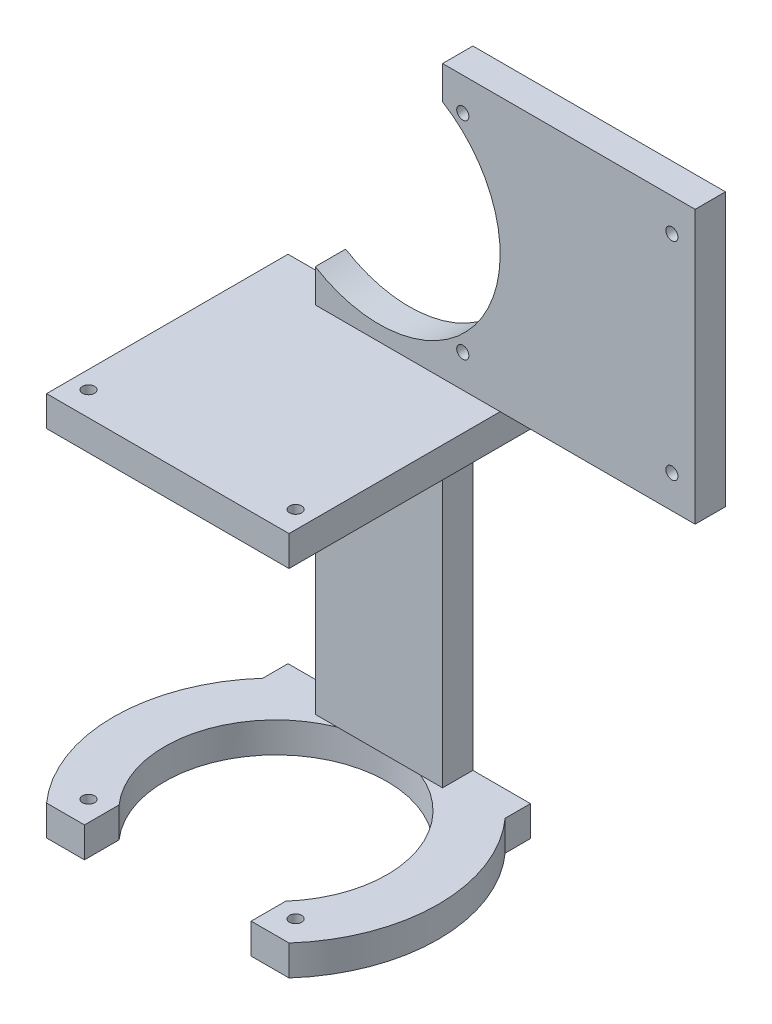
SolidWorks part; units mm, degrees
ref_plane "前视基准面" through (0, 0, 0) normal (0, 0, 1) x (1, 0, 0)
ref_plane "上视基准面" through (0, 0, 0) normal (0, 1, 0) x (1, 0, 0)
ref_plane "右视基准面" through (0, 0, 0) normal (1, 0, 0) x (0, 0, -1)
other "Configuration Table"
sketch "草图1" plane through (0, 0, 0) normal (0, 0, 1) x (1, 0, 0)
  line L1 (0, 0) -> (25, 0)
  line L2 (0, 0) -> (0, 27)
  line L3 (0, 27) -> (25, 27)
  line L4 (25, 0) -> (25, 27)
  dimension "D1" = 27
  dimension "D2" = 25
extrude "凸台-拉伸1" add sketch "草图1" along normal blind 3
sketch "草图2" plane through (0, 0, 3) normal (0, 0, 1) x (1, 0, 0)
  line L0 (0, 13.5) -> (50000, 13.5) construction
  line L1 (0, 27) -> (0, 0) construction
  line L3 (2, 23.75) -> (22.7, 23.75) construction
  line L4 (2, 23.75) -> (2, 3.25) construction
  line L5 (2, 3.25) -> (22.7, 3.25) construction
  line L6 (22.7, 23.75) -> (22.7, 3.25) construction
  circle A0 centre (2, 23.75) radius 0.6
  circle A1 centre (22.7, 23.75) radius 0.6
  circle A2 centre (22.7, 3.25) radius 0.6
  circle A3 centre (2, 3.25) radius 0.6
  circle A4 centre (-6.3, 13.5) radius 12
  point P4 (0, 13.5)
  point P9 (2, 13.5)
  dimension "D4" = 1.2
  dimension "D5" = 1.2
  dimension "D6" = 1.2
  dimension "D7" = 1.2
  dimension "D9" = 24
  dimension "D1" = 20.5
  dimension "D2" = 20.7
  dimension "D3" = 2
  dimension "D8" = 8.3
extrude "切除-拉伸1" cut sketch "草图2" against normal up to next and the other way through all
sketch "草图3" plane through (0, 0, 3) normal (0, 0, 1) x (1, 0, 0)
  line L0 (-6.3, 13.5) -> (-6.3, -49986.5) construction
  line L2 (-12.6, 3.2868) -> (0, 3.2868)
  line L3 (-12.6, 3.2868) -> (-12.6, -38.1)
  line L4 (-12.6, -38.1) -> (0, -38.1)
  line L5 (0, 3.2868) -> (0, 0)
  line L6 (0, 0) -> (25, 0)
  line L7 (25, 0) -> (25, 27)
  line L8 (25, 27) -> (0, 27)
  line L9 (0, 27) -> (0, 23.7132)
  line L10 (0, 3.2868) -> (0, 0)
  line L11 (0, 0) -> (25, 0)
  line L12 (25, 0) -> (25, 27)
  line L13 (25, 27) -> (0, 27)
  line L14 (0, 27) -> (0, 23.7132)
  line L15 (0, 3.2868) -> (0, -38.1)
  circle A0 centre (-6.3, 13.5) radius 12
  arc A1 (0, 3.2868) -> (0, 23.7132) centre (-6.3, 13.5) ccw
  arc A2 (0, 3.2868) -> (0, 23.7132) centre (-6.3, 13.5) ccw
  point P14 (-6.3, 3.2868)
  point P15 (0, 0)
  line M15 (0, 3.2868) -> (0, 0)
  dimension "D2" = 38.1
  dimension "D1" = 0
extrude "凸台-拉伸2" add sketch "草图3" against normal blind 3 contours A0 L0 L4 L15 M15 | L0 A0 L3 L4
sketch "草图4" plane through (0, 0, 3) normal (0, 0, 1) x (1, 0, 0)
  line L0 (-6.3, -21.7132) -> (-6.3, 49978.2868) construction
  line L1 (-12.6, -38.1) -> (0, -38.1) construction
  line L2 (0, 0) -> (25, 0) construction
  line L3 (-18.3, 0) -> (5.7, 0)
  line L4 (-18.3, 0) -> (-18.3, -3)
  line L5 (-18.3, -3) -> (5.7, -3)
  line L6 (5.7, 0) -> (5.7, -3)
  point P4 (-6.3, -38.1)
  point P9 (-6.3, 0)
  dimension "D1" = 24
  dimension "D2" = 3
  dimension "D3" = 0
extrude "凸台-拉伸3" add sketch "草图4" along normal blind 20.9 and the other way up to surface contours L4 L3 L6 L5 other way up to face at (1.4, 3.25, 0)
sketch "草图5" plane through (0, 0, 0) normal (0, 1, 0) x (1, 0, 0)
  line L0 (-6.3, -25) -> (-6.3, 49975) construction
  line L1 (5.7, -23.9) -> (-18.3, -23.9) construction
  line L3 (-16.55, -3) -> (3.95, -3) construction
  line L4 (-16.55, -3) -> (-16.55, -21.5) construction
  line L5 (-16.55, -21.5) -> (3.95, -21.5) construction
  line L6 (3.95, -3) -> (3.95, -21.5) construction
  line L7 (25, -3) -> (0, -3) construction
  circle A0 centre (-16.55, -21.5) radius 0.6
  circle A1 centre (3.95, -21.5) radius 0.6
  point P4 (-6.3, -23.9)
  point P10 (-6.3, -3)
  dimension "D2" = 1.2
  dimension "D3" = 1.2
  dimension "D1" = 18.5
  dimension "D4" = 20.5
extrude "切除-拉伸2" cut sketch "草图5" against normal up to next and the other way through all
ref_plane "基准面3" through (0, -19.05, 0) normal (0, -1, 0) x (-1, 0, 0)
mirror "镜向3" about plane through (0, -19.05, 0) normal (0, -1, 0) of "切除-拉伸2", "凸台-拉伸3"
sketch "草图9" plane through (0, -38.1, 0) normal (0, -1, 0) x (1, 0, 0)
  line L0 (-16.55, 21.5) -> (3.95, 21.5) construction
  line L1 (-6.3, 18.5) -> (-6.3, -49981.5) construction
  line L2 (-14.55, 23.9) -> (-14.55, 20.4758)
  line L3 (-18.3, 23.9) -> (5.7, 23.9) construction
  line L4 (1.95, 23.9) -> (1.95, 20.4758)
  line L5 (-14.55, 23.9) -> (1.95, 23.9)
  circle A0 centre (-6.3, 13.2) radius 11
  point P6 (-6.3, 21.5)
  line M8 (5.7, 23.9) -> (-18.3, 23.9)
  dimension "D1" = 22
  dimension "D2" = 8.3
  dimension "D3" = 2
extrude "切除-拉伸4" cut sketch "草图9" against normal up to surface (3 mm away) contours A0 L5 | A0 L2 M8 | A0 L4 M8 up to face at (3.95, -35.1, 20.9)
sketch "草图10" plane through (0, -38.1, 0) normal (0, -1, 0) x (1, 0, 0)
  line L0 (0, 3) -> (-2.1817, 3) construction
  line L2 (5.7, 23.9) -> (5.7, 0) construction
  line L3 (5.7, 0) -> (0, 0) construction
  line L4 (0, 0) -> (0, 3) construction
  line L6 (-10.4183, 3) -> (-12.6, 3) construction
  line L7 (-12.6, 3) -> (-12.6, 0) construction
  line L8 (-12.6, 0) -> (-18.3, 0) construction
  line L9 (-18.3, 0) -> (-18.3, 23.9) construction
  line L10 (0, 3) -> (-2.1817, 3)
  line L12 (5.7, 23.9) -> (5.7, 0)
  line L13 (5.7, 0) -> (0, 0)
  line L14 (0, 0) -> (0, 3)
  line L16 (-10.4183, 3) -> (-12.6, 3)
  line L17 (-12.6, 3) -> (-12.6, 0)
  line L18 (-12.6, 0) -> (-18.3, 0)
  line L19 (-18.3, 0) -> (-18.3, 23.9)
  line L20 (1.95, 20.4758) -> (1.95, 23.9) construction
  line L21 (1.95, 23.9) -> (5.7, 23.9) construction
  line L22 (-18.3, 23.9) -> (-14.55, 23.9) construction
  line L23 (-14.55, 23.9) -> (-14.55, 20.4758) construction
  line L24 (1.95, 20.4758) -> (1.95, 23.9)
  line L25 (1.95, 23.9) -> (5.7, 23.9)
  line L26 (5.7, 23.9) -> (5.7, 0)
  line L27 (5.7, 0) -> (0, 0)
  line L28 (0, 0) -> (0, 3)
  line L29 (0, 3) -> (-2.1817, 3)
  line L30 (-18.3, 23.9) -> (-14.55, 23.9)
  line L31 (-14.55, 23.9) -> (-14.55, 20.4758)
  line L32 (-10.4183, 3) -> (-12.6, 3)
  line L33 (-12.6, 3) -> (-12.6, 0)
  line L34 (-12.6, 0) -> (-18.3, 0)
  line L35 (-18.3, 0) -> (-18.3, 23.9)
  circle A0 centre (-6.3, 13.2) radius 16.0776
  arc A5 (-2.1817, 3) -> (1.95, 20.4758) centre (-6.3, 13.2) ccw construction
  arc A6 (-14.55, 20.4758) -> (-10.4183, 3) centre (-6.3, 13.2) ccw construction
  arc A7 (-2.1817, 3) -> (1.95, 20.4758) centre (-6.3, 13.2) ccw
  arc A8 (-14.55, 20.4758) -> (-10.4183, 3) centre (-6.3, 13.2) ccw
  line M4 (-18.3, 23.9) -> (-18.3, 0)
extrude "凸台-拉伸4" add sketch "草图10" against normal up to surface (3 mm away) contours A0 M4 | L12 A0 up to face at (-16.55, -35.1, 20.9)
